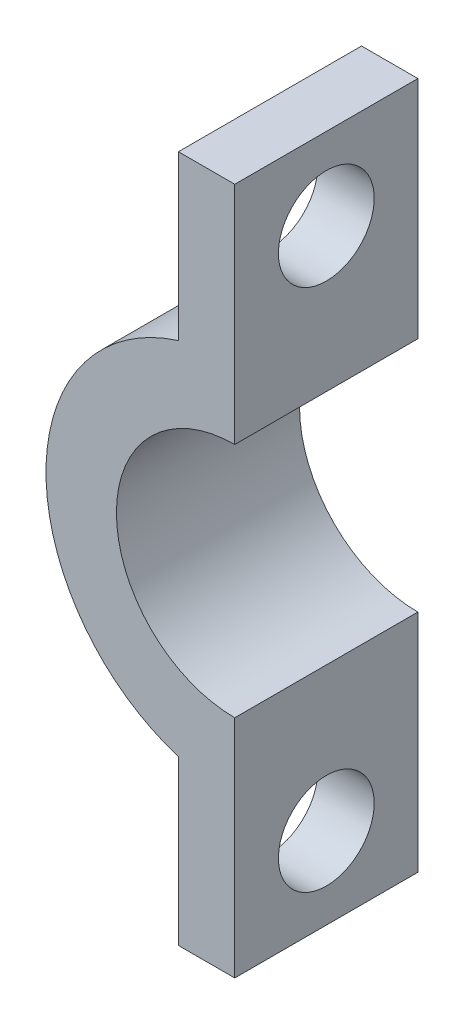
SolidWorks part; units mm, degrees
ref_plane "Piano frontale" through (0, 0, 0) normal (0, 0, 1) x (1, 0, 0)
ref_plane "Piano superiore" through (0, 0, 0) normal (0, 1, 0) x (1, 0, 0)
ref_plane "Piano destro" through (0, 0, 0) normal (1, 0, 0) x (0, 0, -1)
sketch "Schizzo1" plane through (0, 0, 0) normal (0, 0, 1) x (1, 0, 0)
  line L0 (0, 4.2) -> (0, -4.2) construction
  line L1 (0, 4.2) -> (0, 12.2)
  line L2 (-4.2, 0) -> (0, 0) construction
  line L3 (0, -4.2) -> (0, -12.2)
  line L4 (0, 12.2) -> (-2, 12.2)
  line L5 (-2, 12.2) -> (-2, 6.3945)
  line L6 (0, -12.2) -> (-2, -12.2)
  line L7 (-2, -12.2) -> (-2, -6.3945)
  arc A0 (0, 4.2) -> (0, -4.2) centre (0, 0) ccw
  arc A1 (-2, 6.3945) -> (-2, -6.3945) centre (0, 0) ccw
  dimension "D1" = 8.4
  dimension "D3" = 13.4
  dimension "D2" = 8
  dimension "D4" = 2
extrude "Estrusione-Estrusione1" add sketch "Schizzo1" along normal blind 6.5
sketch "Schizzo2" plane through (-2, 0, 0) normal (-1, 0, 0) x (0, 0, 1)
  line L0 (0, 6.3945) -> (6.5, 12.2) construction
  circle A0 centre (3.25, 9.2973) radius 1.7
  dimension "D1" = 3.4
extrude "Taglio-Estrusione1" cut sketch "Schizzo2" against normal blind 6.5
mirror "Specchia1" about plane through (0, 0, 0) normal (0, 1, 0) of "Taglio-Estrusione1"
